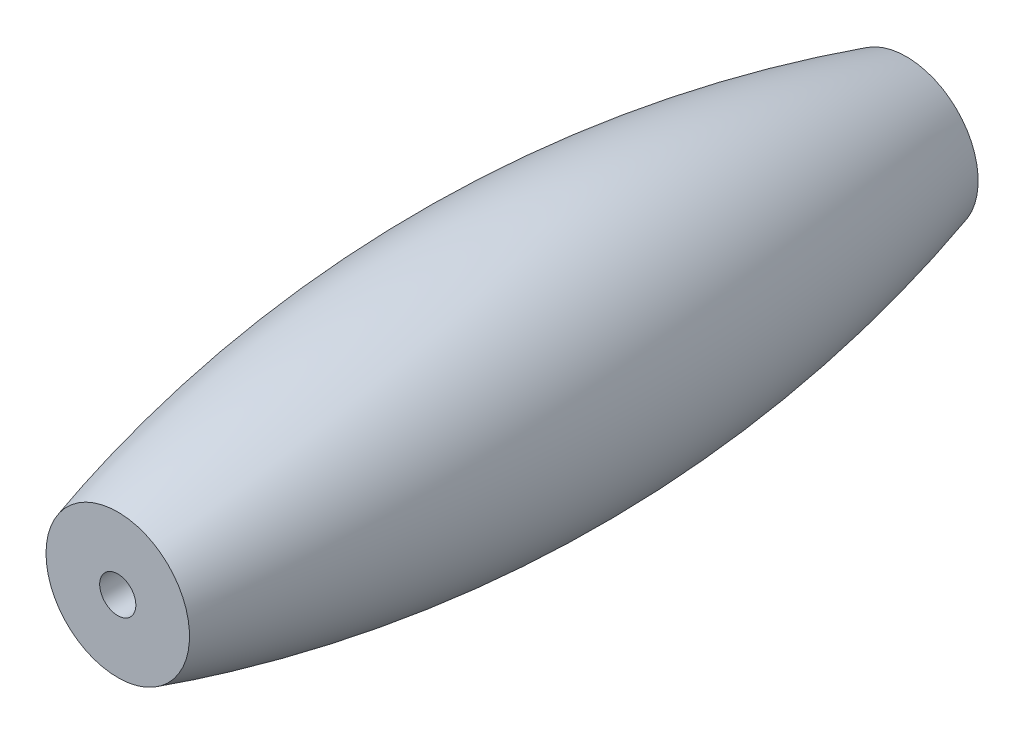
SolidWorks part; units mm, degrees
ref_plane "前视基准面" through (0, 0, 0) normal (0, 0, 1) x (1, 0, 0)
ref_plane "上视基准面" through (0, 0, 0) normal (0, 1, 0) x (1, 0, 0)
ref_plane "右视基准面" through (0, 0, 0) normal (1, 0, 0) x (0, 0, -1)
sketch "草图1" plane through (0, 0, 0) normal (0, 1, 0) x (1, 0, 0)
  line L0 (0, 27.25) -> (0, -27.25)
  line L1 (0, -27.25) -> (4.9589, -27.25)
  line L2 (0, 27.25) -> (4.9589, 27.25)
  arc A3 (4.9589, -27.25) -> (4.9589, 27.25) centre (-88.6019, 0) ccw
  point P4 (0, 0)
revolve "旋转1" add sketch "草图1" angle 360 about L0
sketch "草图2" plane through (0, 0, 27.25) normal (0, 0, 1) x (1, 0, 0)
  circle A0 centre (0, 0) radius 1.25
extrude "切除-拉伸1" cut sketch "草图2" against normal through all
